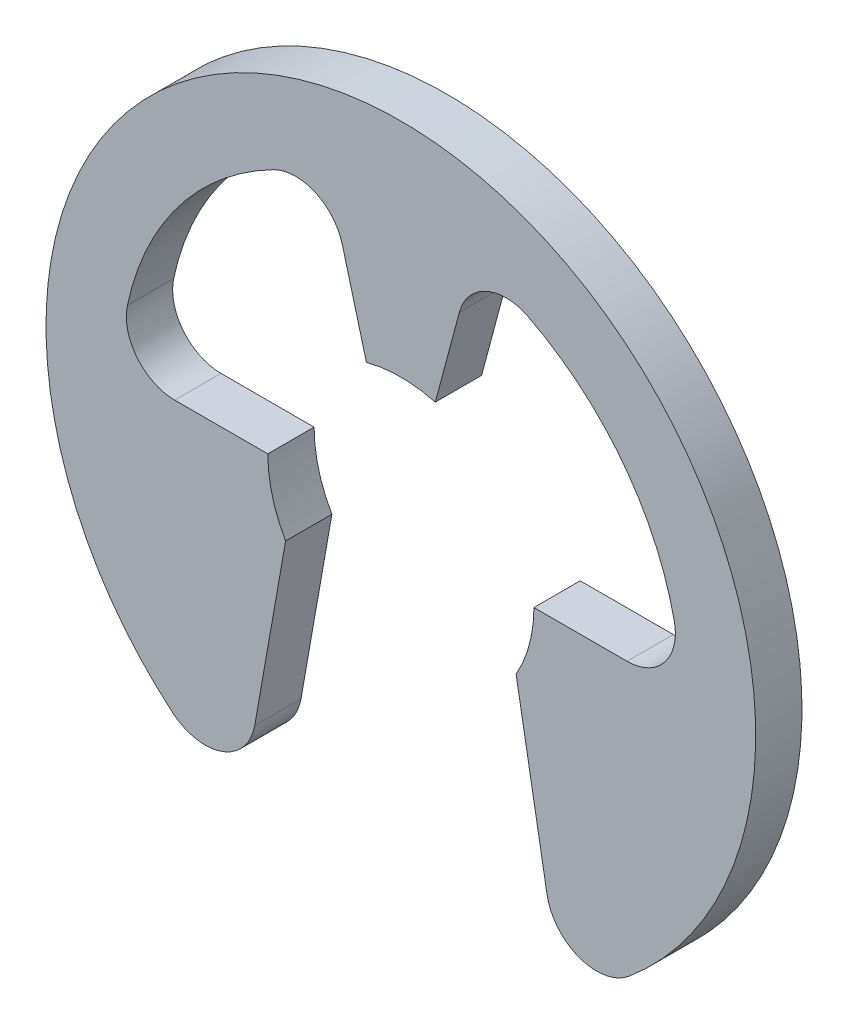
SolidWorks part; units mm, degrees
ref_plane "Plane1" through (0, 0, 0) normal (0, 0, 1) x (1, 0, 0)
ref_plane "Plane2" through (0, 0, 0) normal (0, 1, 0) x (1, 0, 0)
ref_plane "Plane3" through (0, 0, 0) normal (1, 0, 0) x (0, 0, -1)
sketch "Clipboard" plane through (0, 0, 0) normal (0, 0, 1) x (1, 0, 0)
  line L0 (0, 0) -> (0.65, 0)
  circle A0 centre (0, 0) radius 1.05
  circle A1 centre (0, 0) radius 2.8
  dimension "FreeID" = 2.1
  dimension "FreeOD" = 5.6
  dimension "Bridge" = 0.65
sketch "BodySke" plane through (0, 0, 0) normal (0, 0, 1) x (1, 0, 0)
  line L0 (-0.7581, 0) -> (0.7581, 0) construction
  line L1 (0, 0) -> (0, 1.15) construction
  line L2 (0, 0) -> (0.1962, 0.7323) construction
  line L3 (0, 0) -> (0.9959, -0.575) construction
  line L4 (0, 0) -> (-0.1962, 0.7323) construction
  line L5 (0, 0) -> (-0.9959, -0.575) construction
  line L6 (0.9959, -0.575) -> (1.2632, -2.0906)
  line L7 (-0.9959, -0.575) -> (-1.2632, -2.0906)
  line L9 (1.15, 0) -> (1.9545, 0)
  line L10 (-1.15, 0) -> (-1.9545, 0)
  line L11 (0.2976, 1.1108) -> (0.5059, 1.8879)
  line L12 (-0.2976, 1.1108) -> (-0.5059, 1.8879)
  circle A0 centre (0, 0) radius 1.15 construction
  arc A1 (2.3632, 0.5054) -> (1.0998, 2.1519) centre (0, 0) ccw
  arc A2 (1.9721, -2.3485) -> (-1.9721, -2.3485) centre (0, 0) ccw
  arc A3 (0.9959, -0.575) -> (1.15, 0) centre (0, 0) ccw
  arc A4 (-1.0998, 2.1519) -> (-2.3632, 0.5054) centre (0, 0) ccw
  arc A5 (-1.15, 0) -> (-0.9959, -0.575) centre (0, 0) ccw
  arc A6 (-0.2976, 1.1108) -> (0.2976, 1.1108) centre (0, 0) cw
  arc A7 (1.0998, 2.1519) -> (0.5059, 1.8879) centre (0.9096, 1.7797) ccw
  arc A8 (1.2632, -2.0906) -> (1.9721, -2.3485) centre (1.692, -2.0149) ccw
  arc A9 (-1.9721, -2.3485) -> (-1.2632, -2.0906) centre (-1.692, -2.0149) ccw
  arc A10 (-2.3632, 0.5054) -> (-1.9545, 0) centre (-1.9545, 0.418) ccw
  arc A11 (-0.5059, 1.8879) -> (-1.0998, 2.1519) centre (-0.9096, 1.7797) ccw
  arc A12 (1.9545, 0) -> (2.3632, 0.5054) centre (1.9545, 0.418) ccw
  dimension "D1" = 30
  dimension "GrooveDia" = 2.3
  dimension "OutsideDia" = 7.6966
  dimension "D3" = 30
  dimension "TipRad" = 0.5695
  dimension "CavityDia" = 5.9966
  dimension "CavityFilletRad" = 0.4779
  dimension "D4" = 20
extrude "Body" add sketch "BodySke" against normal blind 0.4
equation "' \"FreeID@Clipboard\" = 0.64"
equation "' \"Thickness@Body\" = 0.25"
equation "' \"GrooveDia@BodySke\" = 0.72"
equation "' \"FreeOD@Clipboard\" = 2"
equation "' \"Bridge@Clipboard\" = 0.3"
equation "' \"FreeID@Clipboard\" = 19.5"
equation "' \"Thickness@Body\" = 1.3"
equation "' \"GrooveDia@BodySke\" = 20.00"
equation "' \"FreeOD@Clipboard\" = 37.1"
equation "' \"Bridge@Clipboard\" = 3.3"
equation "\"OutsideDia@BodySke\" = ( \"GrooveDia@BodySke\"  /  \"FreeID@Clipboard\" )  * \"FreeOD@Clipboard\""
equation "\"CavityDia@BodySke\" = \"OutsideDia@BodySke\"  - 2 * \"Bridge@Clipboard\""
equation "\"CavityFilletRad@BodySke\" =  (\"CavityDia@BodySke\" - \"GrooveDia@BodySke\") / 2 * 0.33"
equation "\"TipRad@BodySke\" = 0.67 * \"Bridge@Clipboard\""
